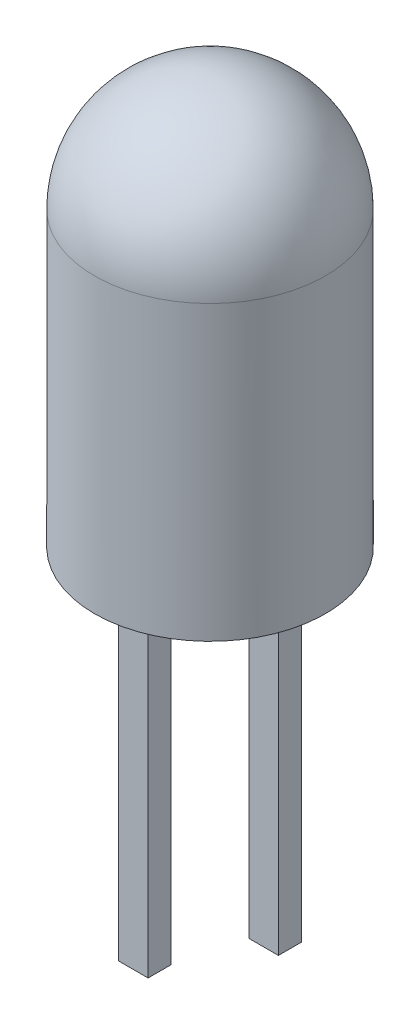
SolidWorks part; units mm, degrees
ref_plane "Front Plane" through (0, 0, 0) normal (0, 0, 1) x (1, 0, 0)
ref_plane "Top Plane" through (0, 0, 0) normal (0, 1, 0) x (1, 0, 0)
ref_plane "Right Plane" through (0, 0, 0) normal (1, 0, 0) x (0, 0, -1)
sketch "Sketch1" plane through (0, 0, 0) normal (0, 0, 1) x (1, 0, 0)
  line L0 (0, 0) -> (0, 27.4114) construction
  line L1 (0, 0) -> (-1.5, 0)
  line L4 (-1.5, 5.3) -> (-6.2879, 5.3) construction
  line L5 (-1.5, 0) -> (-1.5, 3.8)
  line L6 (0, 0) -> (0, 5.3)
  arc A0 (-1.5, 3.8) -> (0, 5.3) centre (0, 3.8) cw
  point P3 (0, 0)
  point P5 (-1.5, 1.2)
  point P7 (-1.5, 0)
  point P9 (-1.5, 3.8)
  point P12 (0, 0)
  point P13 (-6.2879, 5.3)
  point P15 (-1.4, 0)
  dimension "D6" = 1.5
  dimension "D4" = 5.3
  dimension "D7" = 5.3
revolve "Revolve1" add sketch "Sketch1" angle 360 about L6
sketch "Sketch3" plane through (0, 0, 0) normal (0, -1, 0) x (1, 0, 0)
  line L0 (1.5, 0) -> (-1.5, 0) construction
  line L4 (-1.0379, 0.1492) -> (-0.6548, 0.1492)
  line L5 (-1.0379, 0.1492) -> (-1.0379, -0.1492)
  line L6 (-1.0379, -0.1492) -> (-0.6548, -0.1492)
  line L7 (-0.6548, 0.1492) -> (-0.6548, -0.1492)
  line L8 (-1.0379, 0.1492) -> (-0.6548, -0.1492) construction
  line L9 (-1.0379, -0.1492) -> (-0.6548, 0.1492) construction
  line L10 (1.0379, 0.1492) -> (0.6548, 0.1492)
  line L11 (1.0379, 0.1492) -> (1.0379, -0.1492)
  line L12 (1.0379, -0.1492) -> (0.6548, -0.1492)
  line L13 (0.6548, 0.1492) -> (0.6548, -0.1492)
  line L14 (1.0379, 0.1492) -> (0.6548, -0.1492) construction
  line L15 (1.0379, -0.1492) -> (0.6548, 0.1492) construction
  circle A1 centre (0, 0) radius 1.5 construction
  point P2 (0.8463, -0.0863)
  point P3 (0.8463, 0)
  point P9 (-0.8463, 0)
  dimension "D1" = 0.3831
  dimension "D2" = 0.3831
  dimension "D3" = 0.2985
  dimension "D4" = 0.2985
  dimension "D5" = 0.6548
  dimension "D6" = 0.6548
extrude "Boss-Extrude1" add sketch "Sketch3" along normal blind 4 separate body
sketch "Sketch4" plane through (0, 0, 0) normal (0, 0, 1) x (1, 0, 0)
  line L0 (1.0379, 2.2604) -> (0.2941, 2.7888)
  line L1 (-0.5659, 2.6172) -> (-0.5659, 2.7967)
  line L2 (-1.0379, -0.4146) -> (-1.0379, 2.5705) construction
  line L3 (-1.0379, -4) -> (-1.0379, 0) construction
  line L4 (1.0379, -0.4738) -> (1.0379, 2.2604) construction
  line L5 (1.0379, -4) -> (1.0379, 0) construction
  line L6 (0.4821, 1.5513) -> (-0.6659, 2.3668)
  line L7 (1.1181, 2.2034) -> (-0.1026, 3.0706) construction
  line L8 (1.0379, 2.2604) -> (1.0379, 1.5513)
  line L9 (0.4821, 1.5513) -> (-0.6548, 1.5513)
  line L10 (-1.0379, 2.6172) -> (-1.0379, 1.5513)
  line L12 (-0.3857, 2.7069) -> (0.236, 2.7069)
  line L13 (-0.6659, 2.6172) -> (-0.6659, 2.3668)
  line L14 (-0.5659, 2.6172) -> (-0.5659, 2.4185)
  line L15 (0.6548, 1.5513) -> (-0.5659, 2.4185)
  line L16 (0.5969, 1.4697) -> (-0.6659, 2.3668) construction
  line L17 (0.6548, 0) -> (0.6548, 1.5513) construction
  line L18 (0.6548, 1.5513) -> (0.6548, 0)
  line L19 (1.0379, 1.5513) -> (1.0379, 0)
  line L20 (1.0379, 0) -> (0.6548, 0)
  line L21 (-1.0379, 1.5513) -> (-1.0379, 0)
  line L22 (-0.6548, 0) -> (-0.6548, 1.5513)
  line L23 (-1.0379, 0) -> (-0.6548, 0)
  line L24 (-0.6659, 2.6172) -> (-1.0379, 2.6172)
  line L25 (0.236, 2.7069) -> (0.2941, 2.7888)
  line L26 (-0.5659, 2.7967) -> (-0.5127, 2.7967)
  line L27 (-0.5127, 2.7967) -> (-0.3857, 2.7069)
  point P13 (0, 2.0842)
  dimension "D1" = 0.1
  dimension "D2" = 0.8
extrude "Boss-Extrude2" add sketch "Sketch4" along normal mid plane 0.3
sketch "Sketch5" plane through (0, 2.7069, 0) normal (0, 1, 0) x (1, 0, 0)
  circle A0 centre (-0.0606, 0) radius 0.1894
extrude "Boss-Extrude3" add sketch "Sketch5" along normal blind 0.1 separate body
sketch "Sketch7" plane through (0, -4, 0) normal (0, -1, 0) x (1, 0, 0)
  line L4 (-0.6548, -0.1492) -> (-0.6548, 0.1492)
  line L5 (-0.6548, 0.1492) -> (-1.0379, 0.1492)
  line L6 (-1.0379, 0.1492) -> (-1.0379, -0.1492)
  line L7 (-1.0379, -0.1492) -> (-0.6548, -0.1492)
  line L8 (-0.6548, -0.1492) -> (-0.6548, 0.1492)
  line L9 (-0.6548, 0.1492) -> (-1.0379, 0.1492)
  line L10 (-1.0379, 0.1492) -> (-1.0379, -0.1492)
  line L11 (-1.0379, -0.1492) -> (-0.6548, -0.1492)
  dimension "D1" = 0
extrude "Boss-Extrude5" add sketch "Sketch7" along normal blind 1.1
